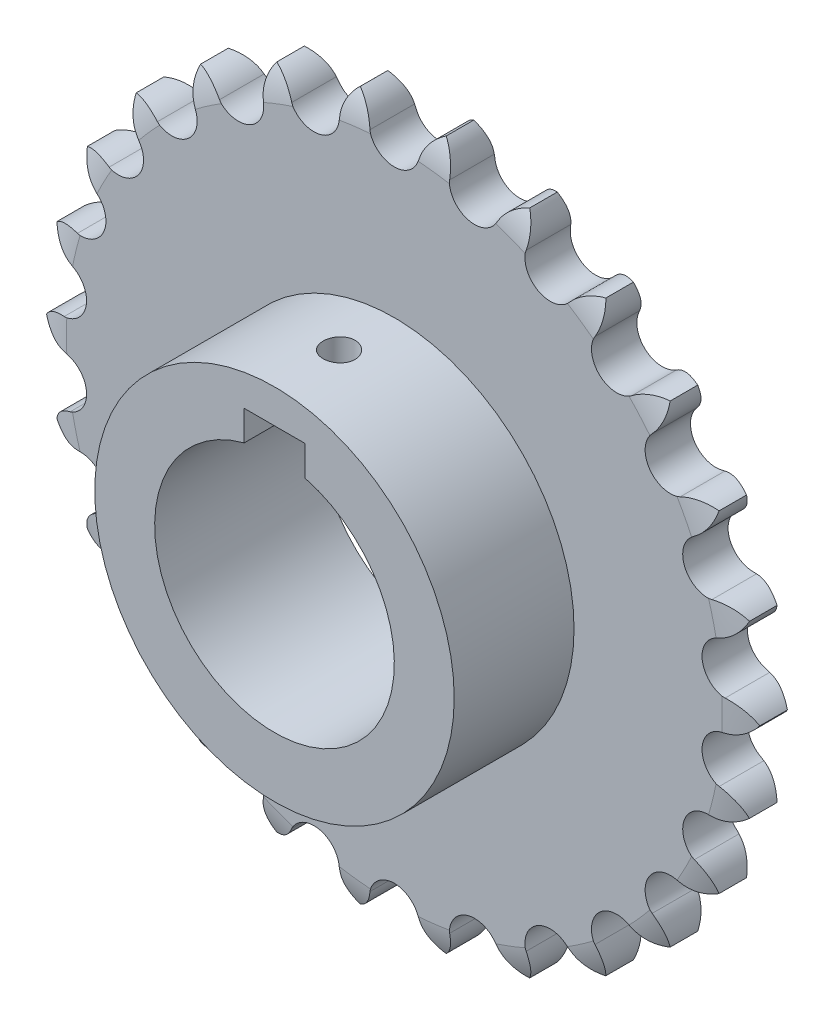
SolidWorks part; units mm, degrees
ref_plane "Front Plane" through (0, 0, 0) normal (0, 0, 1) x (1, 0, 0)
ref_plane "Top Plane" through (0, 0, 0) normal (0, 1, 0) x (1, 0, 0)
ref_plane "Right Plane" through (0, 0, 0) normal (1, 0, 0) x (0, 0, -1)
sketch "Sketch2" plane through (0, 0, 0) normal (0, 0, 1) x (1, 0, 0)
  line L0 (0, 0) -> (0, 56.7055)
  line L1 (0, 0) -> (9.6213, 51.1475) construction
  circle A0 centre (0, 0) radius 52.0446 construction
  circle A1 centre (0, 0) radius 53.34 construction
  arc A2 (2.2775, 56.6597) -> (0, 56.7055) centre (0, 0) ccw construction
  arc A3 (-3.9253, 52.4455) -> (3.9253, 52.4455) centre (0, 53.34) ccw
  arc A5 (6.8497, 56.2903) -> (3.9253, 52.4455) centre (9.6213, 51.1475) ccw
  arc A6 (-2.2775, 56.6597) -> (6.8497, 56.2903) centre (0, 0) ccw construction
  arc A7 (-6.8497, 56.2903) -> (-3.9253, 52.4455) centre (-9.6213, 51.1475) cw
  arc A8 (20.1218, 53.0153) -> (16.3622, 49.9822) centre (21.5821, 47.3588) ccw
  arc A9 (8.7398, 51.8609) -> (16.3622, 49.9822) centre (12.7651, 51.79) ccw
  arc A10 (6.8205, 56.2938) -> (8.7398, 51.8609) centre (2.8987, 51.9638) cw
  arc A11 (32.2245, 46.6593) -> (27.8483, 44.614) centre (32.2887, 40.8177) ccw
  arc A12 (20.897, 48.2624) -> (27.8483, 44.614) centre (24.7883, 47.2302) ccw
  arc A13 (20.0943, 53.0258) -> (20.897, 48.2624) centre (15.2503, 49.7601) cw
  arc A14 (42.4545, 37.5917) -> (37.7159, 36.6531) centre (41.1187, 31.9044) ccw
  arc A15 (31.8397, 41.859) -> (37.7159, 36.6531) centre (35.371, 39.9256) ccw
  arc A16 (32.2003, 46.6761) -> (31.8397, 41.859) centre (26.7155, 44.6646) cw
  arc A17 (50.2171, 26.3393) -> (45.3916, 26.562) centre (47.5591, 21.137) ccw
  arc A18 (40.932, 33.0229) -> (45.3916, 26.562) centre (43.898, 30.3006) ccw
  arc A19 (42.4349, 37.6137) -> (40.932, 33.0229) centre (36.6281, 36.9733) cw
  arc A20 (55.0613, 13.5562) -> (50.4293, 14.9272) centre (51.2355, 9.1411) ccw
  arc A21 (47.6455, 22.2676) -> (50.4293, 14.9272) centre (49.8738, 18.9146) ccw
  arc A22 (50.2034, 26.3654) -> (47.6455, 22.2676) centre (44.412, 27.1332) cw
  arc A23 (56.7055, -0.0147) -> (52.5363, 2.425) centre (51.9343, -3.386) ccw
  arc A24 (51.59, 10.2183) -> (52.5363, 2.425) centre (52.9511, 6.4294) ccw
  arc A25 (55.0542, 13.5848) -> (51.59, 10.2183) centre (49.6149, 15.7163) cw
  arc A26 (55.0542, -13.5848) -> (51.59, -10.2183) centre (49.6149, -15.7163) ccw
  arc A27 (52.5363, -2.425) -> (51.59, -10.2183) centre (52.9511, -6.4294) ccw
  arc A28 (56.7055, 0.0147) -> (52.5363, -2.425) centre (51.9343, 3.386) cw
  arc A29 (50.2034, -26.3654) -> (47.6455, -22.2676) centre (44.412, -27.1332) ccw
  arc A30 (50.4293, -14.9272) -> (47.6455, -22.2676) centre (49.8738, -18.9146) ccw
  arc A31 (55.0613, -13.5562) -> (50.4293, -14.9272) centre (51.2355, -9.1411) cw
  arc A32 (42.4349, -37.6137) -> (40.932, -33.0229) centre (36.6281, -36.9733) ccw
  arc A33 (45.3916, -26.562) -> (40.932, -33.0229) centre (43.898, -30.3006) ccw
  arc A34 (50.2171, -26.3393) -> (45.3916, -26.562) centre (47.5591, -21.137) cw
  arc A35 (32.2003, -46.6761) -> (31.8397, -41.859) centre (26.7155, -44.6646) ccw
  arc A36 (37.7159, -36.6531) -> (31.8397, -41.859) centre (35.371, -39.9256) ccw
  arc A37 (42.4545, -37.5917) -> (37.7159, -36.6531) centre (41.1187, -31.9044) cw
  arc A38 (20.0943, -53.0258) -> (20.897, -48.2624) centre (15.2503, -49.7601) ccw
  arc A39 (27.8483, -44.614) -> (20.897, -48.2624) centre (24.7883, -47.2302) ccw
  arc A40 (32.2245, -46.6593) -> (27.8483, -44.614) centre (32.2887, -40.8177) cw
  arc A41 (6.8205, -56.2938) -> (8.7398, -51.8609) centre (2.8987, -51.9638) ccw
  arc A42 (16.3622, -49.9822) -> (8.7398, -51.8609) centre (12.7651, -51.79) ccw
  arc A43 (20.1218, -53.0153) -> (16.3622, -49.9822) centre (21.5821, -47.3588) cw
  arc A44 (-6.8497, -56.2903) -> (-3.9253, -52.4455) centre (-9.6213, -51.1475) ccw
  arc A45 (3.9253, -52.4455) -> (-3.9253, -52.4455) centre (0, -53.34) ccw
  arc A46 (6.8497, -56.2903) -> (3.9253, -52.4455) centre (9.6213, -51.1475) cw
  arc A47 (-20.1218, -53.0153) -> (-16.3622, -49.9822) centre (-21.5821, -47.3588) ccw
  arc A48 (-8.7398, -51.8609) -> (-16.3622, -49.9822) centre (-12.7651, -51.79) ccw
  arc A49 (-6.8205, -56.2938) -> (-8.7398, -51.8609) centre (-2.8987, -51.9638) cw
  arc A50 (-32.2245, -46.6593) -> (-27.8483, -44.614) centre (-32.2887, -40.8177) ccw
  arc A51 (-20.897, -48.2624) -> (-27.8483, -44.614) centre (-24.7883, -47.2302) ccw
  arc A52 (-20.0943, -53.0258) -> (-20.897, -48.2624) centre (-15.2503, -49.7601) cw
  arc A53 (-42.4545, -37.5917) -> (-37.7159, -36.6531) centre (-41.1187, -31.9044) ccw
  arc A54 (-31.8397, -41.859) -> (-37.7159, -36.6531) centre (-35.371, -39.9256) ccw
  arc A55 (-32.2003, -46.6761) -> (-31.8397, -41.859) centre (-26.7155, -44.6646) cw
  arc A56 (-50.2171, -26.3393) -> (-45.3916, -26.562) centre (-47.5591, -21.137) ccw
  arc A57 (-40.932, -33.0229) -> (-45.3916, -26.562) centre (-43.898, -30.3006) ccw
  arc A58 (-42.4349, -37.6137) -> (-40.932, -33.0229) centre (-36.6281, -36.9733) cw
  arc A59 (-55.0613, -13.5562) -> (-50.4293, -14.9272) centre (-51.2355, -9.1411) ccw
  arc A60 (-47.6455, -22.2676) -> (-50.4293, -14.9272) centre (-49.8738, -18.9146) ccw
  arc A61 (-50.2034, -26.3654) -> (-47.6455, -22.2676) centre (-44.412, -27.1332) cw
  arc A62 (-56.7055, 0.0147) -> (-52.5363, -2.425) centre (-51.9343, 3.386) ccw
  arc A63 (-51.59, -10.2183) -> (-52.5363, -2.425) centre (-52.9511, -6.4294) ccw
  arc A64 (-55.0542, -13.5848) -> (-51.59, -10.2183) centre (-49.6149, -15.7163) cw
  arc A65 (-55.0542, 13.5848) -> (-51.59, 10.2183) centre (-49.6149, 15.7163) ccw
  arc A66 (-52.5363, 2.425) -> (-51.59, 10.2183) centre (-52.9511, 6.4294) ccw
  arc A67 (-56.7055, -0.0147) -> (-52.5363, 2.425) centre (-51.9343, -3.386) cw
  arc A68 (-50.2034, 26.3654) -> (-47.6455, 22.2676) centre (-44.412, 27.1332) ccw
  arc A69 (-50.4293, 14.9272) -> (-47.6455, 22.2676) centre (-49.8738, 18.9146) ccw
  arc A70 (-55.0613, 13.5562) -> (-50.4293, 14.9272) centre (-51.2355, 9.1411) cw
  arc A71 (-42.4349, 37.6137) -> (-40.932, 33.0229) centre (-36.6281, 36.9733) ccw
  arc A72 (-45.3916, 26.562) -> (-40.932, 33.0229) centre (-43.898, 30.3006) ccw
  arc A73 (-50.2171, 26.3393) -> (-45.3916, 26.562) centre (-47.5591, 21.137) cw
  arc A74 (-32.2003, 46.6761) -> (-31.8397, 41.859) centre (-26.7155, 44.6646) ccw
  arc A75 (-37.7159, 36.6531) -> (-31.8397, 41.859) centre (-35.371, 39.9256) ccw
  arc A76 (-42.4545, 37.5917) -> (-37.7159, 36.6531) centre (-41.1187, 31.9044) cw
  arc A77 (-20.0943, 53.0258) -> (-20.897, 48.2624) centre (-15.2503, 49.7601) ccw
  arc A78 (-27.8483, 44.614) -> (-20.897, 48.2624) centre (-24.7883, 47.2302) ccw
  arc A79 (-32.2245, 46.6593) -> (-27.8483, 44.614) centre (-32.2887, 40.8177) cw
  arc A80 (-6.8205, 56.2938) -> (-8.7398, 51.8609) centre (-2.8987, 51.9638) ccw
  arc A81 (-16.3622, 49.9822) -> (-8.7398, 51.8609) centre (-12.7651, 51.79) ccw
  arc A82 (-20.1218, 53.0153) -> (-16.3622, 49.9822) centre (-21.5821, 47.3588) cw
  circle A83 centre (0, 0) radius 19.05
  point P192 (0, 0)
  dimension "D1" = 113.411
  dimension "D2" = 106.68
  dimension "D3" = 104.0892
  dimension "D4" = 8.0518
  dimension "D5" = 26
  dimension "D6" = 38.1
extrude "Boss-Extrude2" add sketch "Sketch2" along normal blind 7.2136
sketch "Sketch3" plane through (0, 0, 7.2136) normal (0, 0, 1) x (1, 0, 0)
  circle A0 centre (0, 0) radius 19.05 construction
  circle A1 centre (0, 0) radius 19.05 construction
  circle A2 centre (0, 0) radius 19.05
  circle A3 centre (0, 0) radius 19.05
  circle A4 centre (0, 0) radius 28.575
  dimension "D1" = 57.15
extrude "Boss-Extrude3" add sketch "Sketch3" along normal blind 19.05 contours A4 A2
sketch "Sketch4" plane through (0, 0, 26.2636) normal (0, 0, 1) x (1, 0, 0)
  line L0 (0, 0) -> (0, 41.5692)
  line L2 (-4.826, 18.3716) -> (4.826, 18.3716)
  line L3 (-4.826, 18.3716) -> (-4.826, 23.1976)
  line L4 (-4.826, 23.1976) -> (4.826, 23.1976)
  line L5 (4.826, 18.3716) -> (4.826, 23.1976)
  line L6 (-4.826, 18.3716) -> (4.826, 23.1976) construction
  line L7 (-4.826, 23.1976) -> (4.826, 18.3716) construction
  point P3 (0, 20.7846)
  circle M5 centre (0, 0) radius 19.05
  dimension "D1" = 9.652
  dimension "D2" = 4.826
extrude "Cut-Extrude1" cut sketch "Sketch4" against normal blind 32.258 contours L4 L3 L0 M5 | L5 L4 L0 M5
sketch "Sketch5" plane through (0, 23.1976, 0) normal (0, -1, 0) x (1, 0, 0)
  line L0 (0, -0.3698) -> (0, 0)
  line L1 (-4.826, 0) -> (4.826, 0) construction
  line L2 (0, 0) -> (0, 26.2636)
  line L3 (-4.826, 26.2636) -> (4.826, 26.2636) construction
  circle A0 centre (0, 16.002) radius 2.54
  point P4 (0, 16.002)
  dimension "D2" = 5.08
  dimension "D1" = 16.002
extrude "Cut-Extrude2" cut sketch "Sketch5" against normal blind 8.636 contours L2 A0 | L2 A0
sketch "Sketch7" plane through (0, 0, 0) normal (1, 0, 0) x (0, 0, -1)
  line L0 (-3.6068, 56.2817) -> (-3.6068, 49.3793) construction
  line L1 (0, 0) -> (-40.5089, 0) construction
  line L2 (1.7157, 56.896) -> (-1.524, 56.896)
  line L3 (-7.2136, 56.2817) -> (0, 56.2817) construction
  line L4 (-5.6896, 57.7573) -> (-5.6896, 48.896) construction
  line L5 (-7.2136, 49.3141) -> (-8.9293, 49.3141)
  line L6 (-8.9293, 49.3141) -> (-8.9293, 56.896)
  line L7 (-8.9293, 56.896) -> (-5.6896, 56.896)
  line L8 (1.7157, 49.3141) -> (1.7157, 56.896)
  line L9 (0, 49.3141) -> (1.7157, 49.3141)
  arc A0 (-5.6896, 56.896) -> (-7.2136, 49.3141) centre (5.4082, 50.7212) ccw
  arc A1 (-1.524, 56.896) -> (0, 49.3141) centre (-12.6218, 50.7212) cw
  dimension "D2" = 12.7
  dimension "D1" = 1.524
  dimension "D3" = 56.896
  dimension "D4" = 49.3141
  dimension "D5" = 8.9293
revolve "Cut-Revolve1" cut sketch "Sketch7" angle 360 about L1
